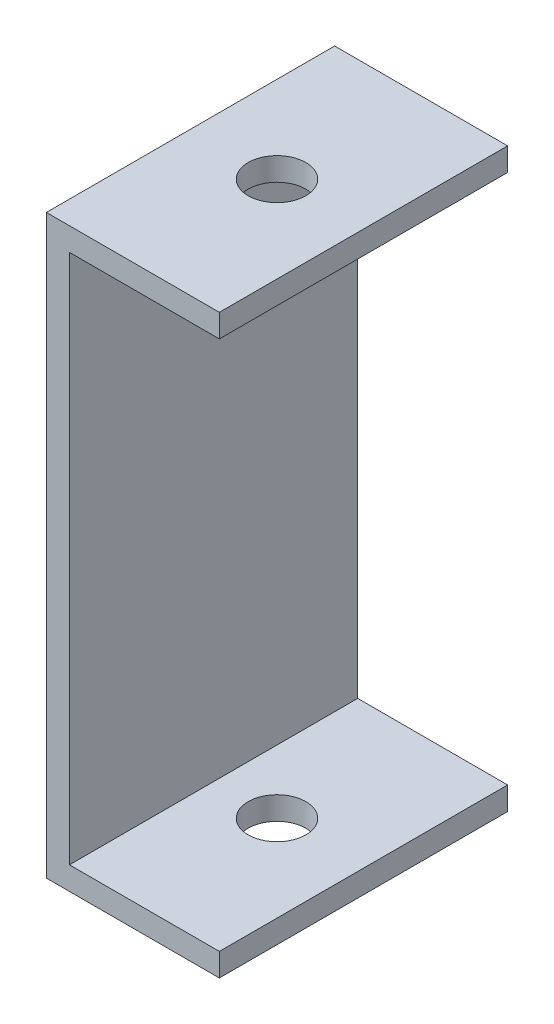
SolidWorks part; units mm, degrees
ref_plane "Alzado" through (0, 0, 0) normal (0, 0, 1) x (1, 0, 0)
ref_plane "Planta" through (0, 0, 0) normal (0, 1, 0) x (1, 0, 0)
ref_plane "Vista lateral" through (0, 0, 0) normal (1, 0, 0) x (0, 0, -1)
sketch "Croquis1" plane through (0, 0, 0) normal (0, 0, 1) x (1, 0, 0)
  line L0 (15, 0) -> (0, 0)
  line L1 (0, 0) -> (0, 50)
  line L2 (0, 50) -> (15, 50)
  line L3 (15, 50) -> (15, 48)
  line L4 (15, 48) -> (2, 48)
  line L5 (2, 48) -> (2, 2)
  line L6 (2, 2) -> (15, 2)
  line L7 (15, 2) -> (15, 0)
  dimension "D1" = 50
  dimension "D2" = 15
  dimension "D3" = 2
  dimension "D4" = 2
extrude "Saliente-Extruir1" add sketch "Croquis1" along normal blind 25
sketch "Croquis2" plane through (0, 50, 0) normal (0, 1, 0) x (1, 0, 0)
  line L1 (15, 0) -> (0, 0) construction
  line L2 (0, -25) -> (0, 0) construction
  circle A0 centre (7.5, -12.5) radius 2.5
  point P7 (0, -12.5)
  point P10 (7.5, 0)
  dimension "D1" = 5
extrude "Cortar-Extruir1" cut sketch "Croquis2" against normal through all
